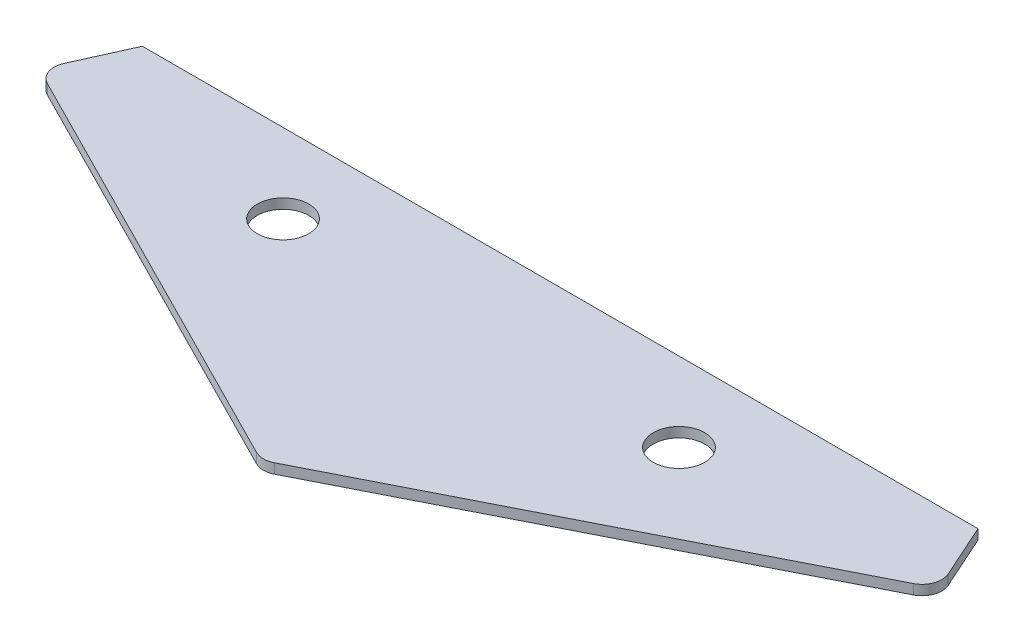
SolidWorks part; units mm, degrees
material "ASTM A36 Steel"
ref_plane "Front Plane" through (0, 0, 0) normal (0, 0, 1) x (1, 0, 0)
ref_plane "Top Plane" through (0, 0, 0) normal (0, 1, 0) x (1, 0, 0)
ref_plane "Right Plane" through (0, 0, 0) normal (1, 0, 0) x (0, 0, -1)
sketch "Sketch1" plane through (0, 0, 0) normal (0, 1, 0) x (1, 0, 0)
  line L0 (248.0329, 52.5933) -> (260.3056, 25.2785)
  line L1 (41.5206, -96.2553) -> (255.7035, 12.2597)
  line L8 (32.4816, -96.2553) -> (-181.7012, 12.2597)
  line L9 (-174.0307, 52.5933) -> (-186.3033, 25.2785)
  line L10 (-174.0307, 52.5933) -> (248.0329, 52.5933)
  arc A0 (260.3056, 25.2785) -> (255.7035, 12.2597) centre (251.184, 21.1802) cw
  arc A1 (32.4816, -96.2553) -> (41.5206, -96.2553) centre (37.0011, -87.3348) ccw
  arc A5 (-186.3033, 25.2785) -> (-181.7012, 12.2597) centre (-177.1817, 21.1802) ccw
  point P18 (-190.2147, 16.5731)
  dimension "D1" = 10
extrude "Boss-Extrude1" add sketch "Sketch1" along normal blind 5
sketch "Sketch2" plane through (0, 5, 0) normal (0, 1, 0) x (1, 0, 0)
  line L0 (248.0329, 52.5933) -> (-174.0307, 52.5933) construction
  circle A0 centre (137.0011, 12.5933) radius 13
  circle A1 centre (-62.9989, 12.5933) radius 13
  point P6 (37.0011, 52.5933)
  dimension "D1" = 26
  dimension "D2" = 100
  dimension "D3" = 40
  dimension "D4" = 26
  dimension "D5" = 40
  dimension "D6" = 100
extrude "Cut-Extrude1" cut sketch "Sketch2" against normal blind 5
